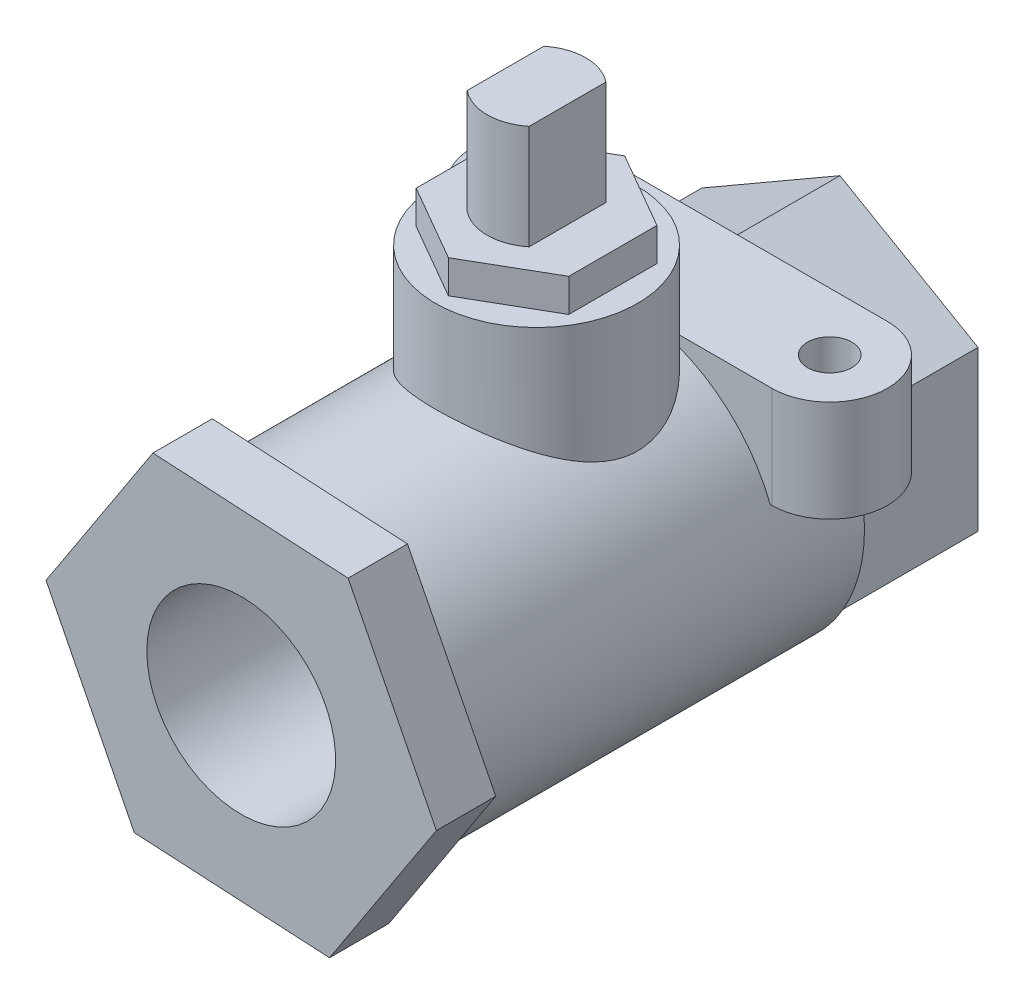
SolidWorks part; units mm, degrees
material "Cast Stainless Steel"
ref_plane "Front Plane" through (0, 0, 0) normal (0, 0, 1) x (1, 0, 0)
ref_plane "Top Plane" through (0, 0, 0) normal (0, 1, 0) x (1, 0, 0)
ref_plane "Right Plane" through (0, 0, 0) normal (1, 0, 0) x (0, 0, -1)
sketch "Sketch1" plane through (0, 0, 0) normal (0, 0, 1) x (1, 0, 0)
  circle A0 centre (0, 0) radius 15.0114
  dimension "D1" = 30.0228
extrude "Boss-Extrude1" add sketch "Sketch1" along normal blind 38.1
sketch "Sketch2" plane through (0, 0, 38.1) normal (0, 0, 1) x (1, 0, 0)
  line L1 (-8.3145, 16.4272) -> (-18.3836, 1.0131)
  line L2 (-18.3836, 1.0131) -> (-10.0691, -15.4142)
  line L3 (-10.0691, -15.4142) -> (8.3145, -16.4272)
  line L4 (8.3145, -16.4272) -> (18.3836, -1.0131)
  line L5 (18.3836, -1.0131) -> (10.0691, 15.4142)
  line L6 (10.0691, 15.4142) -> (-8.3145, 16.4272)
  circle A0 centre (0, 0) radius 15.9448 construction
  dimension "D1" = 31.8897
extrude "Boss-Extrude2" add sketch "Sketch2" along normal blind 5.588
sketch "Sketch3" plane through (0, 0, 0) normal (0, 0, -1) x (-1, 0, 0)
  line L1 (0, 15.0114) -> (-13.0003, 7.5057)
  line L2 (-13.0003, 7.5057) -> (-13.0003, -7.5057)
  line L3 (-13.0003, -7.5057) -> (0, -15.0114)
  line L4 (0, -15.0114) -> (13.0003, -7.5057)
  line L5 (13.0003, -7.5057) -> (13.0003, 7.5057)
  line L6 (13.0003, 7.5057) -> (0, 15.0114)
  circle A0 centre (0, 0) radius 13.0003 construction
  circle A1 centre (0, 0) radius 15.0114 construction
extrude "Boss-Extrude3" add sketch "Sketch3" along normal blind 12.7
ref_plane "Plane1" through (0, 15.0114, 0) normal (0, 1, 0) x (1, 0, 0)
sketch "Sketch5" plane through (0, 15.0114, 0) normal (0, 1, 0) x (1, 0, 0)
  line L0 (-14.1351, -2.4003) -> (14.1351, -2.4003) construction
  line L1 (-14.1351, 3.048) -> (14.1351, 3.048)
  line L2 (-14.1351, -7.8486) -> (14.1351, -7.8486)
  line L3 (-13.0003, 12.7) -> (0, 12.7) construction
  arc A0 (-14.1351, 3.048) -> (-14.1351, -7.8486) centre (-14.1351, -2.4003) ccw
  arc A1 (14.1351, -7.8486) -> (14.1351, 3.048) centre (14.1351, -2.4003) ccw
  point P2 (0, -2.4003)
  dimension "D3" = 28.2702
  dimension "D1" = 9.652
  dimension "D2" = 10.8966
extrude "Boss-Extrude4" add sketch "Sketch5" against normal blind 9.5504
sketch "Sketch4" plane through (0, 0, -12.7) normal (0, 0, -1) x (-1, 0, 0)
  circle A0 centre (0, 0) radius 8.89
  dimension "D1" = 17.78
extrude "Cut-Extrude1" cut sketch "Sketch4" against normal through all
sketch "Sketch6" plane through (0, 15.0114, 0) normal (0, 1, 0) x (1, 0, 0)
  line L0 (0, 12.7) -> (13.0003, 12.7) construction
  circle A0 centre (0, -15.875) radius 9.525
  dimension "D1" = 19.05
  dimension "D2" = 28.575
extrude "Boss-Extrude5" add sketch "Sketch6" along normal blind 8.636 and the other way blind 5.08
sketch "Sketch7" plane through (0, 23.6474, 0) normal (0, 1, 0) x (1, 0, 0)
  line L1 (0, -7.5748) -> (-7.1882, -11.7249)
  line L2 (-7.1882, -11.7249) -> (-7.1882, -20.0251)
  line L3 (-7.1882, -20.0251) -> (0, -24.1752)
  line L4 (0, -24.1752) -> (7.1882, -20.0251)
  line L5 (7.1882, -20.0251) -> (7.1882, -11.7249)
  line L6 (7.1882, -11.7249) -> (0, -7.5748)
  circle A0 centre (0, -15.875) radius 7.1882 construction
  dimension "D1" = 14.3764
extrude "Boss-Extrude6" add sketch "Sketch7" along normal blind 3.1115
sketch "Sketch8" plane through (0, 26.7589, 0) normal (0, 1, 0) x (1, 0, 0)
  line L1 (-2.921, -19.4907) -> (2.921, -19.4907)
  line L2 (-2.921, -19.4907) -> (-2.921, -12.2593)
  line L3 (-2.921, -12.2593) -> (2.921, -12.2593)
  line L4 (2.921, -19.4907) -> (2.921, -12.2593)
  line L5 (-2.921, -19.4907) -> (2.921, -12.2593) construction
  line L6 (-2.921, -12.2593) -> (2.921, -19.4907) construction
  circle A0 centre (0, -15.875) radius 4.6482
  circle A1 centre (0, -15.875) radius 9.525
  circle A2 centre (0, -15.875) radius 9.525 construction
  dimension "D3" = 9.2964
  dimension "D2" = 5.842
  dimension "D1" = 0
extrude "Boss-Extrude7" add sketch "Sketch8" along normal blind 9.8298 contours L1 L4 L3 L2 | L3 A0 | L1 A0
sketch "Sketch9" plane through (0, 15.0114, 0) normal (0, 1, 0) x (1, 0, 0)
  line L4 (5.1286, -7.8486) -> (14.1351, -7.8486)
  line L5 (14.1351, 3.048) -> (0, 3.048)
  line L6 (0, 3.048) -> (-14.1351, 3.048)
  line L7 (-14.1351, -7.8486) -> (-5.1286, -7.8486)
  line L8 (5.1286, -7.8486) -> (14.1351, -7.8486)
  line L9 (14.1351, 3.048) -> (0, 3.048)
  line L10 (0, 3.048) -> (-14.1351, 3.048)
  line L11 (-14.1351, -7.8486) -> (-5.1286, -7.8486)
  circle A0 centre (-14.1351, -2.4003) radius 2.0892
  circle A1 centre (14.1351, -2.4003) radius 2.0891
  arc A3 (5.1286, -7.8486) -> (-5.1286, -7.8486) centre (0, -15.875) ccw
  arc A4 (14.1351, -7.8486) -> (14.1351, 3.048) centre (14.1351, -2.4003) ccw
  arc A5 (-14.1351, 3.048) -> (-14.1351, -7.8486) centre (-14.1351, -2.4003) ccw
  arc A6 (5.1286, -7.8486) -> (-5.1286, -7.8486) centre (0, -15.875) ccw
  arc A7 (14.1351, -7.8486) -> (14.1351, 3.048) centre (14.1351, -2.4003) ccw
  arc A8 (-14.1351, 3.048) -> (-14.1351, -7.8486) centre (-14.1351, -2.4003) ccw
  dimension "D2" = 4.1783
  dimension "D1" = 0
extrude "Cut-Extrude2" cut sketch "Sketch9" against normal blind 8.89 contours A1 | A0
